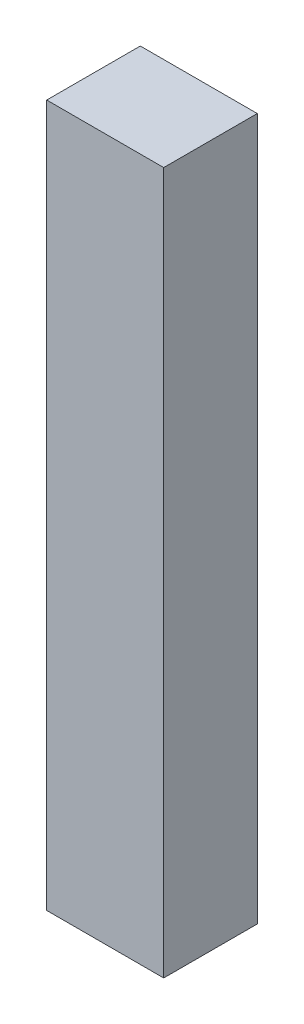
SolidWorks part; units mm, degrees
ref_plane "Front Plane" through (0, 0, 0) normal (0, 0, 1) x (1, 0, 0)
ref_plane "Top Plane" through (0, 0, 0) normal (0, 1, 0) x (1, 0, 0)
ref_plane "Right Plane" through (0, 0, 0) normal (1, 0, 0) x (0, 0, -1)
sketch "Sketch1" plane through (0, 0, 0) normal (0, 1, 0) x (1, 0, 0)
  line L1 (-12.5, 10) -> (12.5, 10)
  line L2 (-12.5, 10) -> (-12.5, -10)
  line L3 (-12.5, -10) -> (12.5, -10)
  line L4 (12.5, 10) -> (12.5, -10)
  line L5 (-12.5, 10) -> (12.5, -10) construction
  line L6 (-12.5, -10) -> (12.5, 10) construction
  point P0 (0, 0)
  dimension "D1" = 25
  dimension "D2" = 20
extrude "Boss-Extrude1" add sketch "Sketch1" along normal mid plane 150
